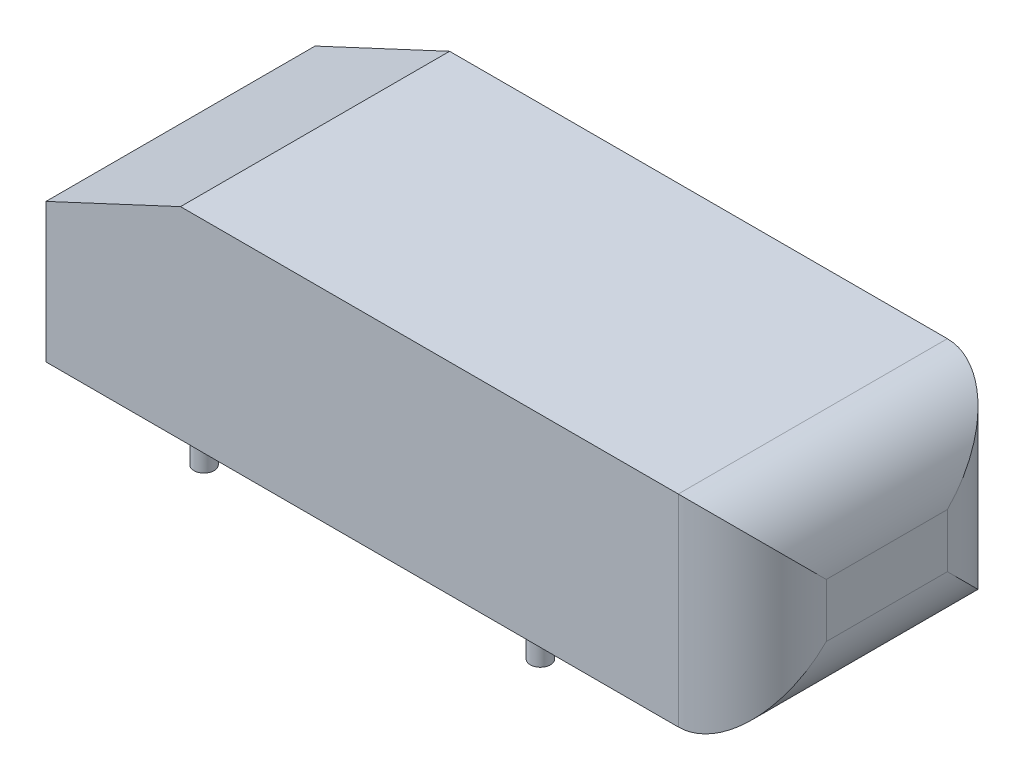
SolidWorks part; units mm, degrees
ref_plane "Front Plane"
ref_plane "Top Plane" through (0, 0, 0) normal (0, 1, 0) x (1, 0, 0)
ref_plane "Right Plane" through (0, 0, 0) normal (1, 0, 0) x (0, 0, -1)
sketch "Sketch3" plane through (0, 0, 0) normal (1, 0, 0) x (0, 0, -1)
  line L1 (200, 350) -> (-200, 350)
  line L2 (200, 350) -> (200, 50)
  line L3 (200, 50) -> (-200, 50)
  line L4 (-200, 350) -> (-200, 50)
  dimension "D1" = 400
  dimension "D2" = 300
  dimension "D3" = 50
  dimension "D4" = 200
extrude "Boss-Extrude2" add sketch "Sketch3" against normal blind 1050
fillet "Fillet1" radius 110 4 edges at (0, 350, 0) (0, 200, -200) (0, 50, 0) (0, 200, 200)
chamfer "Chamfer1" distance 200 angle 25 1 edges at (-1050, 350, 0)
sketch "Sketch4" plane through (0, 50, 0) normal (0, -1, 0) x (1, 0, 0)
  line L0 (-979.1924, 0) -> (-144.3774, 0) construction
  line L1 (-1050, 200) -> (-1050, -200) construction
  circle A0 centre (-850, 165) radius 15
  circle A1 centre (-350, 165) radius 15
  circle A2 centre (-350, -165) radius 15
  circle A3 centre (-850, -165) radius 15
  dimension "D1" = 30
  dimension "D2" = 165
  dimension "D3" = 200
  dimension "D4" = 500
extrude "Boss-Extrude3" add sketch "Sketch4" along normal blind 50
